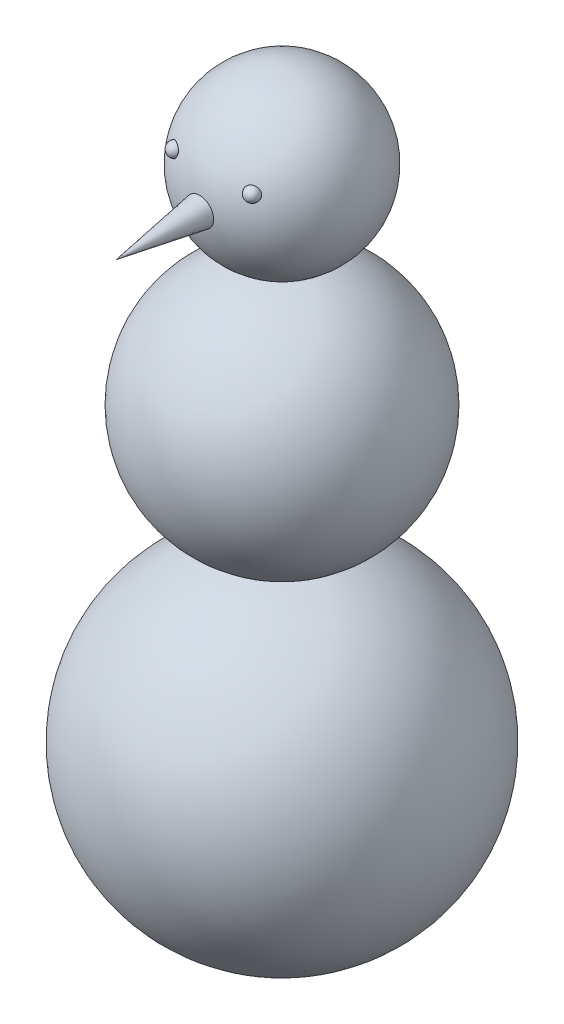
SolidWorks part; units mm, degrees
ref_plane "Front Plane" through (0, 0, 0) normal (0, 0, 1) x (1, 0, 0)
ref_plane "Top Plane" through (0, 0, 0) normal (0, 1, 0) x (1, 0, 0)
ref_plane "Right Plane" through (0, 0, 0) normal (1, 0, 0) x (0, 0, -1)
sketch "Sketch1" plane through (0, 0, 0) normal (0, 0, 1) x (1, 0, 0)
  line L0 (0, -304.8) -> (0, 304.8)
  arc A0 (0, 304.8) -> (0, -304.8) centre (0, 0) cw
  point P4 (0, 0)
  dimension "D1" = 609.6
revolve "Bottom" add sketch "Sketch1" angle 360 about L0
sketch "Sketch2" plane through (0, 0, 0) normal (0, 0, 1) x (1, 0, 0)
  line L0 (0, 0) -> (0, 1219.2) construction
  line L1 (0, 304.8) -> (0, 762)
  arc A2 (0, 762) -> (0, 304.8) centre (0, 533.4) cw
  dimension "D1" = 1219.2
  dimension "D2" = 304.8
  dimension "D3" = 457.2
revolve "Middle" add sketch "Sketch2" angle 360 about L1
sketch "Sketch3" plane through (0, 0, 0) normal (0, 0, 1) x (1, 0, 0)
  line L0 (0, -304.8) -> (0, 914.4) construction
  line L1 (0, 762) -> (0, 1066.8)
  circle A0 centre (0, 0) radius 304.8 construction
  circle A1 centre (0, 533.4) radius 228.6 construction
  arc A2 (0, 1066.8) -> (0, 762) centre (0, 914.4) cw
  dimension "D1" = 1219.2
  dimension "D2" = 304.8
revolve "Top" add sketch "Sketch3" angle 360 about L0
ref_plane "Nose Plane" through (0, 914.4, 0) normal (0, 1, 0) x (1, 0, 0)
sketch "Sketch5" plane through (0, 914.4, 0) normal (0, 1, 0) x (1, 0, 0)
  line L0 (25.4, -150.2684) -> (0, -150.2684)
  line L1 (0, -150.2684) -> (0, -302.6684)
  line L2 (0, -302.6684) -> (25.4, -150.2684)
  circle A0 centre (0, 0) radius 152.4
  circle A1 centre (0, 0) radius 152.4
  dimension "D1" = 152.4
  dimension "D2" = 25.4
revolve "Revolve4" add sketch "Sketch5" angle 360 about L1
ref_plane "Plane3" through (0, 965.2, 0) normal (0, 1, 0) x (1, 0, 0)
sketch "Sketch7" plane through (0, 965.2, 0) normal (0, 1, 0) x (1, 0, 0)
  line L0 (76.2, -136.5392) -> (65.0656, -113.7097)
  circle A0 centre (0, 0) radius 143.6841
  arc A1 (65.0656, -113.7097) -> (76.2, -136.5392) centre (70.6328, -125.1245) cw
  circle A2 centre (0, 0) radius 143.6841
  point P6 (70.6328, -125.1245)
  dimension "D2" = 12.7
  dimension "D1" = 76.2
  dimension "D3" = 45
revolve "Revolve5" add sketch "Sketch7" angle 360 about L0
mirror "Mirror1" about plane through (0, 0, 0) normal (1, 0, 0) of "Revolve5"
